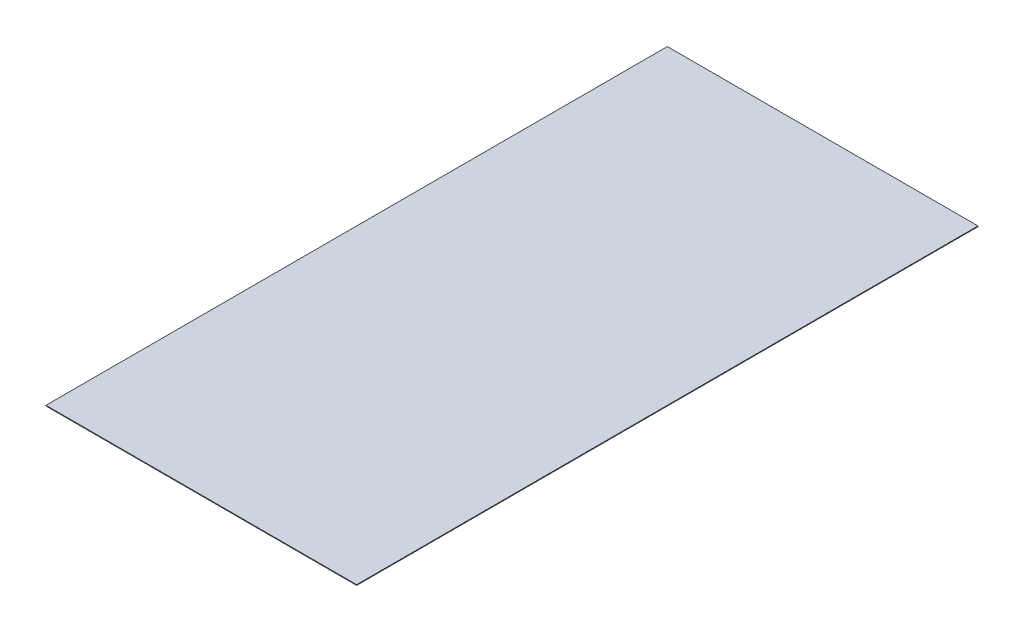
SolidWorks part; units mm, degrees
material "ASTM A36 Acero"
ref_plane "Alzado" through (0, 0, 0) normal (0, 0, 1) x (1, 0, 0)
ref_plane "Planta" through (0, 0, 0) normal (0, 1, 0) x (1, 0, 0)
ref_plane "Vista lateral" through (0, 0, 0) normal (1, 0, 0) x (0, 0, -1)
sketch "Croquis1" plane through (0, 0, 0) normal (0, 1, 0) x (1, 0, 0)
  line L1 (-609.6, -1219.2) -> (609.6, -1219.2)
  line L2 (-609.6, -1219.2) -> (-609.6, 1219.2)
  line L3 (-609.6, 1219.2) -> (609.6, 1219.2)
  line L4 (609.6, -1219.2) -> (609.6, 1219.2)
  line L5 (-609.6, -1219.2) -> (609.6, 1219.2) construction
  line L6 (-609.6, 1219.2) -> (609.6, -1219.2) construction
  point P0 (0, 0)
  dimension "D1" = 2438.4
  dimension "D2" = 1219.2
extrude "Saliente-Extruir1" add sketch "Croquis1" along normal blind 2.7
